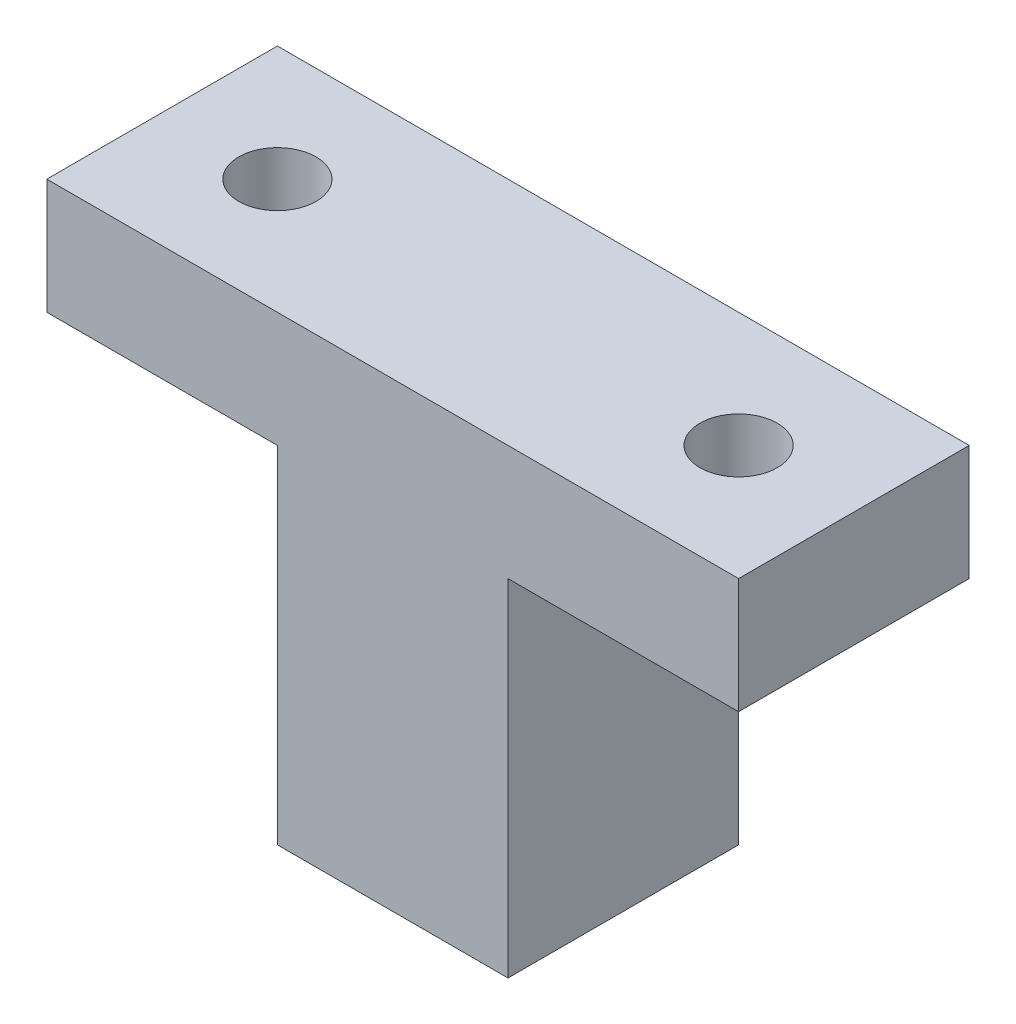
SolidWorks part; units mm, degrees
ref_plane "正面" through (0, 0, 0) normal (0, 0, 1) x (1, 0, 0)
ref_plane "平面" through (0, 0, 0) normal (0, 1, 0) x (1, 0, 0)
ref_plane "右側面" through (0, 0, 0) normal (1, 0, 0) x (0, 0, -1)
sketch "ｽｹｯﾁ1" plane through (0, 0, 0) normal (0, 0, 1) x (1, 0, 0)
  line L0 (-15, 0) -> (15, 0)
  line L1 (0, 0) -> (0, -20) construction
  line L2 (5, -20) -> (-5, -20)
  line L3 (-5, -20) -> (-5, -5)
  line L4 (-5, -5) -> (-15, -5)
  line L5 (-15, -5) -> (-15, 0)
  line L6 (15, -5) -> (15, 0)
  line L7 (5, -5) -> (15, -5)
  line L8 (5, -20) -> (5, -5)
  dimension "D1" = 30
  dimension "D2" = 10
  dimension "D3" = 5
  dimension "D4" = 20
extrude "ﾎﾞｽ - 押し出し1" add sketch "ｽｹｯﾁ1" along normal blind 10
sketch "ｽｹｯﾁ2" plane through (0, -5, 0) normal (0, -1, 0) x (1, 0, 0)
  line L0 (15, 5) -> (-15, 5) construction
  line L1 (15, 10) -> (15, 0) construction
  line L2 (-15, 10) -> (-15, 0) construction
  line L3 (0, 10) -> (0, 0) construction
  line L4 (-5, 10) -> (5, 10) construction
  circle A0 centre (-10, 5) radius 1.675
  circle A1 centre (10, 5) radius 1.675
  dimension "D1" = 3.35
  dimension "D2" = 5
extrude "ｶｯﾄ - 押し出し1" cut sketch "ｽｹｯﾁ2" against normal through all and the other way through all
